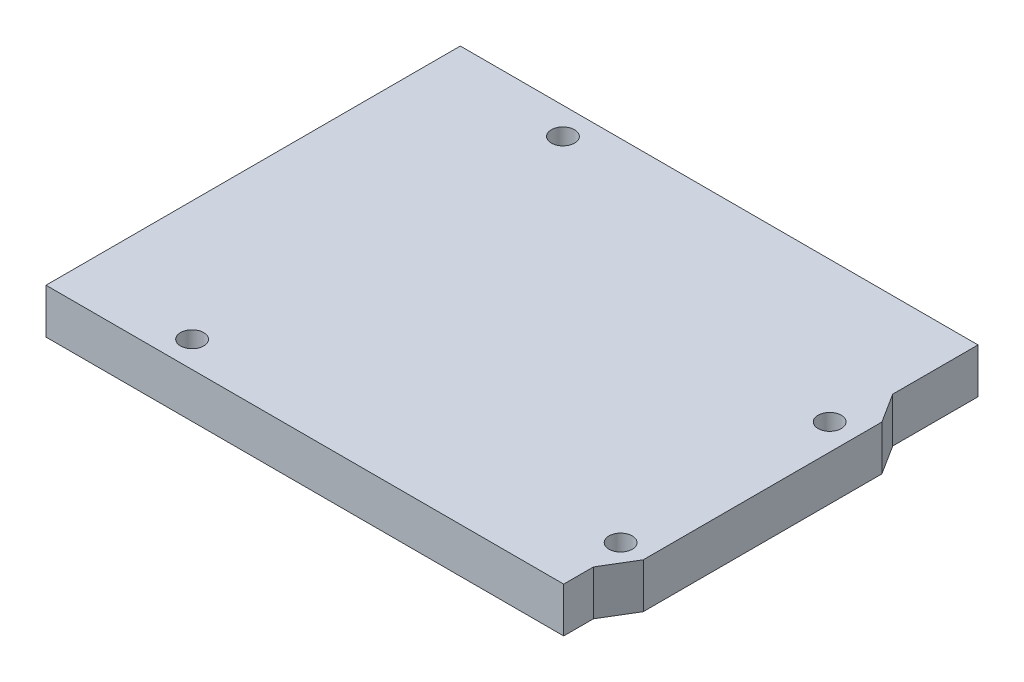
SolidWorks part; units mm, degrees
ref_plane "Front Plane" through (0, 0, 0) normal (0, 0, 1) x (1, 0, 0)
ref_plane "Top Plane" through (0, 0, 0) normal (0, 1, 0) x (1, 0, 0)
ref_plane "Right Plane" through (0, 0, 0) normal (1, 0, 0) x (0, 0, -1)
sketch "Sketch1" plane through (0, 0, 0) normal (0, 1, 0) x (1, 0, 0)
  line L0 (34.55, 16.2707) -> (37.05, 12.3214)
  line L1 (-34.55, -27.65) -> (34.55, -27.65)
  line L2 (-34.55, -27.65) -> (-34.55, 27.65)
  line L3 (-34.55, 27.65) -> (34.55, 27.65)
  line L4 (34.55, -27.65) -> (34.55, -23.6861)
  line L5 (-34.55, -27.65) -> (34.55, 27.65) construction
  line L6 (-34.55, 27.65) -> (34.55, -27.65) construction
  line L7 (37.05, 12.3214) -> (37.05, -19.5297)
  line L8 (37.05, -19.5297) -> (34.55, -23.6861)
  line L9 (34.55, 16.2707) -> (34.55, 27.65)
  circle A0 centre (-17.25, 24.05) radius 1.55
  circle A1 centre (33.55, 8.85) radius 1.55
  circle A2 centre (33.55, -19.05) radius 1.55
  circle A3 centre (-18.55, -24.15) radius 1.55
  point P0 (0, 0)
  dimension "D4" = 3.1
  dimension "D5" = 3.1
  dimension "D6" = 3.1
  dimension "D7" = 3.1
  dimension "D1" = 69.1
  dimension "D2" = 71.6
  dimension "D3" = 55.3
  dimension "D8" = 48.2
  dimension "D9" = 17.3
  dimension "D10" = 16
  dimension "D11" = 27.9
  dimension "D12" = 8.6
  dimension "D13" = 50.8
  dimension "D14" = 3.5
extrude "Boss-Extrude1" add sketch "Sketch1" along normal blind 6
